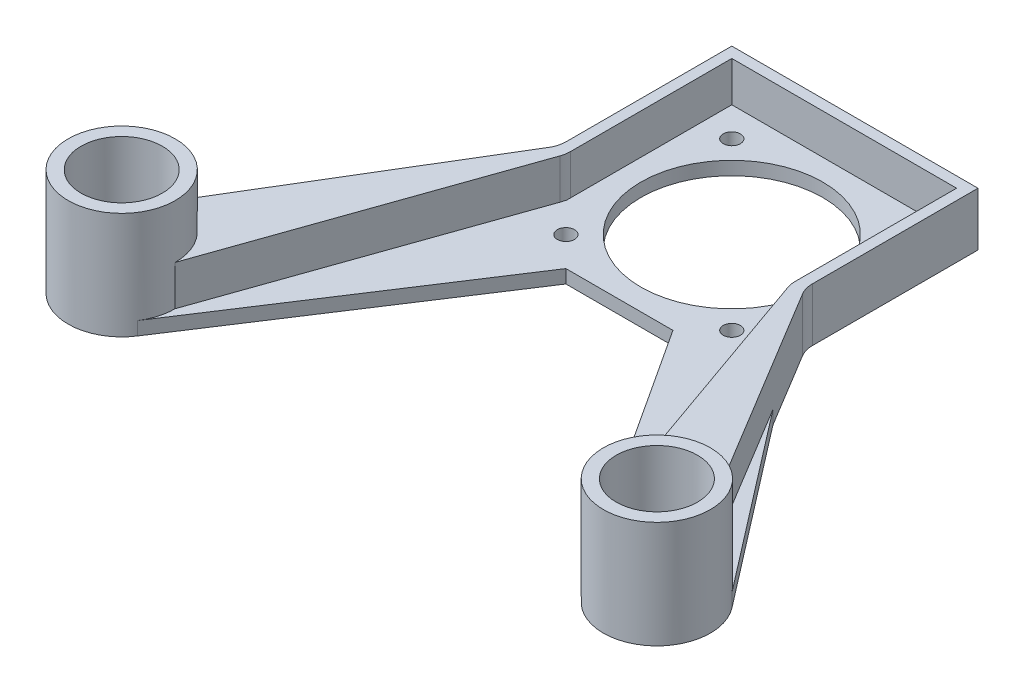
SolidWorks part; units mm, degrees
ref_plane "前视基准面" through (0, 0, 0) normal (0, 0, 1) x (1, 0, 0)
ref_plane "上视基准面" through (0, 0, 0) normal (0, 1, 0) x (1, 0, 0)
ref_plane "右视基准面" through (0, 0, 0) normal (1, 0, 0) x (0, 0, -1)
sketch "草图6" plane through (0, 0, 0) normal (0, 1, 0) x (1, 0, 0)
  line L1 (-21, -21) -> (21, -21)
  line L2 (-21, -21) -> (-21, 21)
  line L3 (-21, 21) -> (21, 21)
  line L4 (21, -21) -> (21, 21)
  line L5 (0, 21) -> (0, -21) construction
  line L6 (-21, 0) -> (21, 0) construction
  circle A0 centre (15.5, 15.5) radius 1.6
  circle A1 centre (-15.5, 15.5) radius 1.6
  circle A2 centre (-15.5, -15.5) radius 1.6
  circle A3 centre (15.5, -15.5) radius 1.6
  circle A4 centre (0, 0) radius 17
  point P0 (0, 0)
extrude "凸台-拉伸1" add sketch "草图6" along normal blind 2.5
sketch "草图7" plane through (0, 2.5, 0) normal (0, 1, 0) x (1, 0, 0)
  line L3 (-21, -10) -> (-57.92, -57.8948)
  line L7 (-10, -21) -> (-41.6253, -69.4648)
  line L8 (10, -21) -> (41.6253, -69.4648)
  line L9 (21, -10) -> (57.92, -57.8948)
  circle A4 centre (-50, -64) radius 7.6
  circle A5 centre (50, -64) radius 7.6
  arc A6 (-57.92, -57.8948) -> (-41.6253, -69.4648) centre (-50, -64) ccw
  arc A7 (41.6253, -69.4648) -> (57.92, -57.8948) centre (50, -64) ccw
  dimension "D3" = 15.2
  dimension "D4" = 15.2
  dimension "D5" = 20
  dimension "D6" = 20
extrude "凸台-拉伸5" add sketch "草图7" against normal blind 2.5
sketch "草图9" plane through (0, 0, 0) normal (0, -1, 0) x (-1, 0, 0)
  circle A0 centre (50, -64) radius 7.6
  circle A1 centre (50, -64) radius 10
  circle A2 centre (-50, -64) radius 7.6
  circle A3 centre (-50, -64) radius 10
extrude "凸台-拉伸7" add sketch "草图9" against normal blind 20
sketch "草图10" plane through (0, 0, 0) normal (0, 1, 0) x (1, 0, 0)
  line L1 (-50, -54) -> (-23.7206, -10.5112)
  line L3 (-40, -64) -> (-21.2834, -10.8056)
  line L4 (23.7206, -10.5112) -> (50, -54)
  line L5 (21.2834, -10.8056) -> (40, -64)
  line L6 (0, 23) -> (23, 23)
  line L7 (0, 23) -> (-23, 23)
  line L10 (-23, -7.9252) -> (-23, 23)
  line L12 (23, 23) -> (23, -7.9252)
  line L15 (-21, -9.146) -> (-21, 21)
  line L16 (-21, 21) -> (21, 21)
  line L17 (21, 21) -> (21, -9.146)
  circle A1 centre (-50, -64) radius 10 construction
  arc A2 (-41.6253, -69.4648) -> (-57.92, -57.8948) centre (-50, -64) ccw construction
  arc A9 (50, -54) -> (40, -64) centre (50, -64) ccw
  arc A10 (-40, -64) -> (-50, -54) centre (-50, -64) ccw
  arc A11 (23, -7.9252) -> (23.7206, -10.5112) centre (28, -7.9252) ccw
  arc A12 (21, -9.146) -> (21.2834, -10.8056) centre (26, -9.146) ccw
  arc A13 (-21.2834, -10.8056) -> (-21, -9.146) centre (-26, -9.146) ccw
  arc A14 (-23.7206, -10.5112) -> (-23, -7.9252) centre (-28, -7.9252) ccw
  point P19 (21, -10)
  point P23 (-21, -10)
  dimension "D1" = 5
extrude "凸台-拉伸11" add sketch "草图10" along normal blind 10
